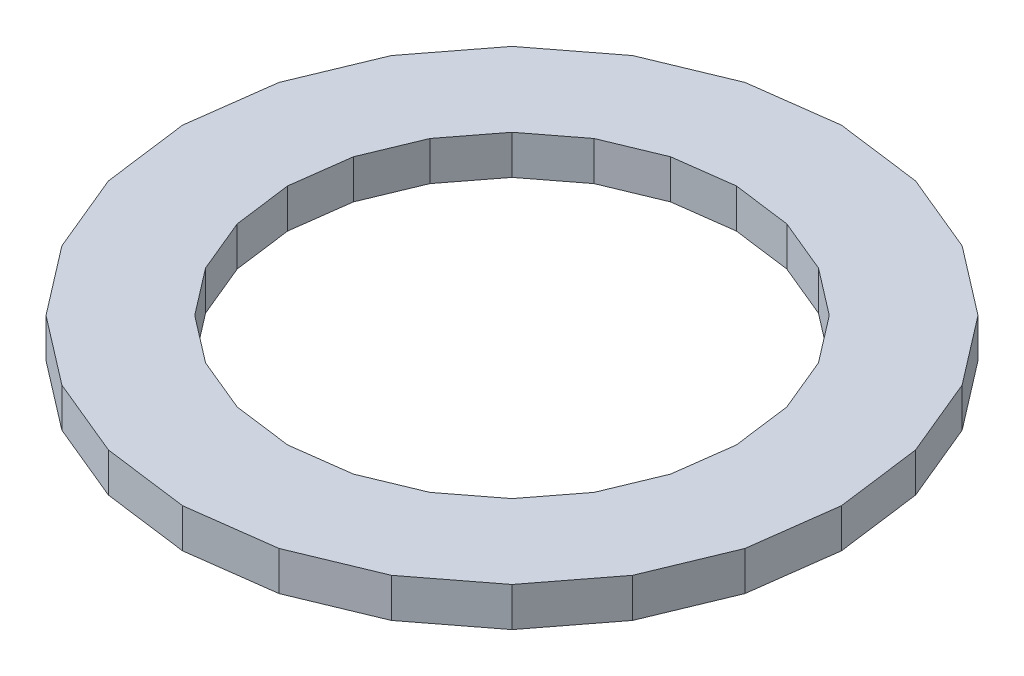
SolidWorks part; units mm, degrees
ref_plane "Front Plane" through (0, 0, 0) normal (0, 0, 1) x (1, 0, 0)
ref_plane "Top Plane" through (0, 0, 0) normal (0, 1, 0) x (1, 0, 0)
ref_plane "Right Plane" through (0, 0, 0) normal (1, 0, 0) x (0, 0, -1)
sketch "Sketch2" plane through (0, 0, 0) normal (0, 1, 0) x (1, 0, 0)
  line L1 (-160.5425, 0) -> (-155.0721, -41.5515)
  line L2 (-155.0721, -41.5515) -> (-139.0339, -80.2712)
  line L3 (-139.0339, -80.2712) -> (-113.5207, -113.5207)
  line L4 (-113.5207, -113.5207) -> (-80.2712, -139.0339)
  line L5 (-80.2712, -139.0339) -> (-41.5515, -155.0721)
  line L6 (-41.5515, -155.0721) -> (0, -160.5425)
  line L7 (0, -160.5425) -> (41.5515, -155.0721)
  line L8 (41.5515, -155.0721) -> (80.2712, -139.0339)
  line L9 (80.2712, -139.0339) -> (113.5207, -113.5207)
  line L10 (113.5207, -113.5207) -> (139.0339, -80.2712)
  line L11 (139.0339, -80.2712) -> (155.0721, -41.5515)
  line L12 (155.0721, -41.5515) -> (160.5425, 0)
  line L13 (160.5425, 0) -> (155.0721, 41.5515)
  line L14 (155.0721, 41.5515) -> (139.0339, 80.2712)
  line L15 (139.0339, 80.2712) -> (113.5207, 113.5207)
  line L16 (113.5207, 113.5207) -> (80.2712, 139.0339)
  line L17 (80.2712, 139.0339) -> (41.5515, 155.0721)
  line L18 (41.5515, 155.0721) -> (0, 160.5425)
  line L19 (0, 160.5425) -> (-41.5515, 155.0721)
  line L20 (-41.5515, 155.0721) -> (-80.2712, 139.0339)
  line L21 (-80.2712, 139.0339) -> (-113.5207, 113.5207)
  line L22 (-113.5207, 113.5207) -> (-139.0339, 80.2712)
  line L23 (-139.0339, 80.2712) -> (-155.0721, 41.5515)
  line L24 (-155.0721, 41.5515) -> (-160.5425, 0)
  line L25 (-109.3041, 0) -> (-105.5797, -28.29)
  line L26 (-105.5797, -28.29) -> (-94.6602, -54.6521)
  line L27 (-94.6602, -54.6521) -> (-77.2897, -77.2897)
  line L28 (-77.2897, -77.2897) -> (-54.6521, -94.6602)
  line L29 (-54.6521, -94.6602) -> (-28.29, -105.5797)
  line L30 (-28.29, -105.5797) -> (0, -109.3041)
  line L31 (0, -109.3041) -> (28.29, -105.5797)
  line L32 (28.29, -105.5797) -> (54.6521, -94.6602)
  line L33 (54.6521, -94.6602) -> (77.2897, -77.2897)
  line L34 (77.2897, -77.2897) -> (94.6602, -54.6521)
  line L35 (94.6602, -54.6521) -> (105.5797, -28.29)
  line L36 (105.5797, -28.29) -> (109.3041, 0)
  line L37 (109.3041, 0) -> (105.5797, 28.29)
  line L38 (105.5797, 28.29) -> (94.6602, 54.6521)
  line L39 (94.6602, 54.6521) -> (77.2897, 77.2897)
  line L40 (77.2897, 77.2897) -> (54.6521, 94.6602)
  line L41 (54.6521, 94.6602) -> (28.29, 105.5797)
  line L42 (28.29, 105.5797) -> (0, 109.3041)
  line L43 (0, 109.3041) -> (-28.29, 105.5797)
  line L44 (-28.29, 105.5797) -> (-54.6521, 94.6602)
  line L45 (-54.6521, 94.6602) -> (-77.2897, 77.2897)
  line L46 (-77.2897, 77.2897) -> (-94.6602, 54.6521)
  line L47 (-94.6602, 54.6521) -> (-105.5797, 28.29)
  line L48 (-105.5797, 28.29) -> (-109.3041, 0)
  circle A0 centre (0, 0) radius 159.169 construction
  circle A1 centre (0, 0) radius 108.369 construction
  dimension "D1" = 41.91
  dimension "D2" = 50.8
extrude "Boss-Extrude2" add sketch "Sketch2" along normal blind 19.05
